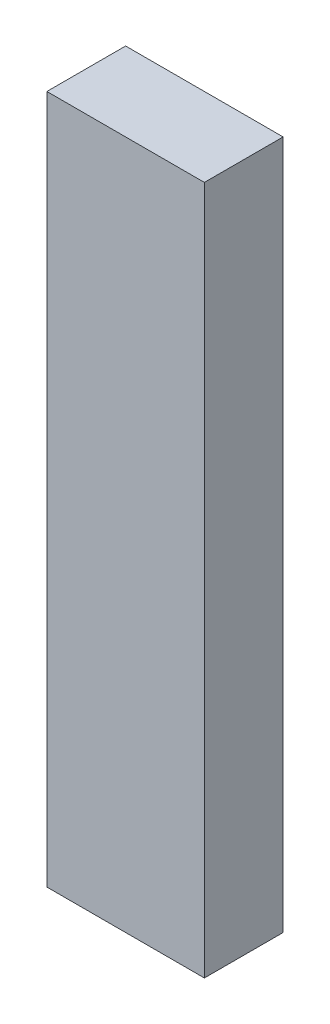
SolidWorks part; units mm, degrees
material "Alloy Steel"
ref_plane "Front Plane" through (0, 0, 0) normal (0, 0, 1) x (1, 0, 0)
ref_plane "Top Plane" through (0, 0, 0) normal (0, 1, 0) x (1, 0, 0)
ref_plane "Right Plane" through (0, 0, 0) normal (1, 0, 0) x (0, 0, -1)
sketch "Sketch1" plane through (0, 0, 0) normal (0, 0, 1) x (1, 0, 0)
  line L1 (5.08, 22.225) -> (-5.08, 22.225)
  line L2 (5.08, 22.225) -> (5.08, -22.225)
  line L3 (5.08, -22.225) -> (-5.08, -22.225)
  line L4 (-5.08, 22.225) -> (-5.08, -22.225)
  line L5 (5.08, 22.225) -> (-5.08, -22.225) construction
  line L6 (5.08, -22.225) -> (-5.08, 22.225) construction
  point P0 (0, 0)
  dimension "D1" = 10.16
  dimension "D2" = 44.45
extrude "Boss-Extrude1" add sketch "Sketch1" along normal blind 5.08
scale "Scale1" [suppressed]
